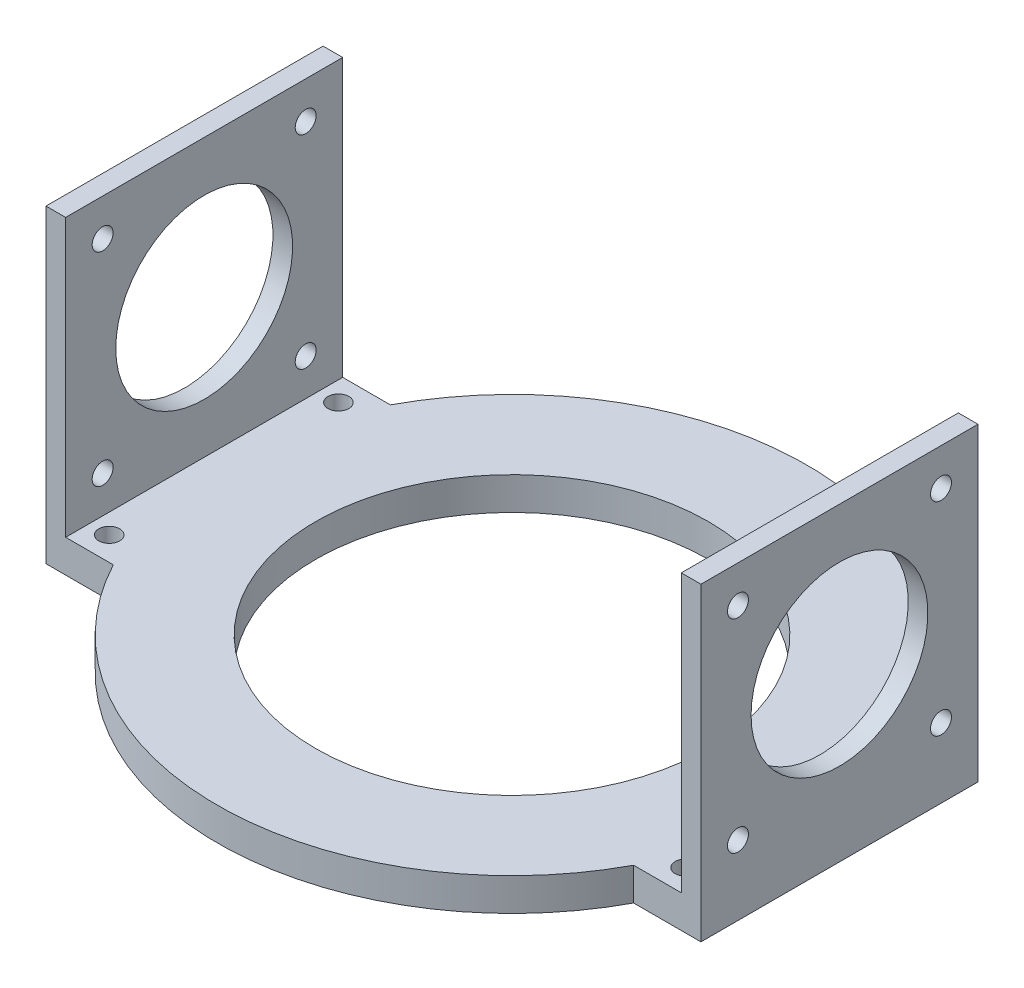
SolidWorks part; units mm, degrees
ref_plane "Front Plane" through (0, 0, 0) normal (0, 0, 1) x (1, 0, 0)
ref_plane "Top Plane" through (0, 0, 0) normal (0, 1, 0) x (1, 0, 0)
ref_plane "Right Plane" through (0, 0, 0) normal (1, 0, 0) x (0, 0, -1)
sketch "Sketch1" plane through (0, 0, 0) normal (0, 1, 0) x (1, 0, 0)
  line L0 (0, 0) -> (-45, 0) construction
  line L1 (0, 0) -> (45, 0) construction
  line L2 (-45, 0) -> (-33, 0) construction
  line L3 (45, 0) -> (33, 0) construction
  line L4 (-16, 21.15) -> (-50, 21.15)
  line L5 (-16, 21.15) -> (-16, -21.15)
  line L6 (-50, 21.15) -> (-50, -21.15)
  line L7 (-16, -21.15) -> (-50, -21.15)
  line L8 (-16, 21.15) -> (-50, -21.15) construction
  line L9 (-50, 21.15) -> (-16, -21.15) construction
  line L10 (16, 21.15) -> (50, 21.15)
  line L11 (16, 21.15) -> (16, -21.15)
  line L12 (50, 21.15) -> (50, -21.15)
  line L13 (16, -21.15) -> (50, -21.15)
  line L14 (16, 21.15) -> (50, -21.15) construction
  line L15 (50, 21.15) -> (16, -21.15) construction
  circle A0 centre (0, 0) radius 45
  circle A1 centre (0, 0) radius 40
  dimension "D1" = 90
  dimension "D8" = 80
  dimension "D2" = 12
  dimension "D3" = 12
  dimension "D4" = 34
  dimension "D5" = 34
  dimension "D6" = 42.3
  dimension "D7" = 42.3
extrude "body" add sketch "Sketch1" along normal blind 5
sketch "Sketch4" plane through (0, 5, 0) normal (0, 1, 0) x (1, 0, 0)
  line L0 (-39.72, -21.15) -> (-50, -21.15) construction
  line L1 (-50, 21.15) -> (-47, 21.15)
  line L2 (-50, 21.15) -> (-50, -21.15)
  line L3 (-50, -21.15) -> (-47, -21.15)
  line L4 (-47, 21.15) -> (-47, -21.15)
  line L5 (39.72, -21.15) -> (50, -21.15) construction
  line L6 (50, 21.15) -> (47, 21.15)
  line L7 (50, 21.15) -> (50, -21.15)
  line L8 (50, -21.15) -> (47, -21.15)
  line L9 (47, 21.15) -> (47, -21.15)
  dimension "D1" = 3
  dimension "D2" = 3
extrude "extrude-wing" add sketch "Sketch4" along normal blind 42.3
sketch "Sketch5" plane through (-50, 0, 0) normal (-1, 0, 0) x (0, 0, 1)
  line L0 (21.15, 47.3) -> (21.15, 0) construction
  line L1 (-21.15, 47.3) -> (21.15, 47.3) construction
  line L2 (-21.15, 47.3) -> (-21.15, 5) construction
  line L3 (-21.15, 5) -> (21.15, 5) construction
  line L4 (21.15, 47.3) -> (21.15, 5) construction
  line L5 (0, 47.3) -> (0, 26.15) construction
  line L7 (-15.5, 41.65) -> (15.5, 41.65) construction
  line L8 (-15.5, 41.65) -> (-15.5, 10.65) construction
  line L9 (-15.5, 10.65) -> (15.5, 10.65) construction
  line L10 (15.5, 41.65) -> (15.5, 10.65) construction
  line L11 (-15.5, 41.65) -> (15.5, 10.65) construction
  line L12 (-15.5, 10.65) -> (15.5, 41.65) construction
  circle A0 centre (-15.5, 41.65) radius 1.6
  circle A1 centre (15.5, 41.65) radius 1.6
  circle A2 centre (15.5, 10.65) radius 1.6
  circle A3 centre (-15.5, 10.65) radius 1.6
  circle A4 centre (0, 26.15) radius 13.5
  dimension "D5" = 3.2
  dimension "D6" = 3.2
  dimension "D7" = 3.2
  dimension "D8" = 3.2
  dimension "D9" = 27
  dimension "D1" = 42.3
  dimension "D2" = 21.15
  dimension "D3" = 31
  dimension "D4" = 31
extrude "cut-motor-holes" cut sketch "Sketch5" against normal through all
sketch "Sketch8" plane through (0, 0, 0) normal (0, -1, 0) x (1, 0, 0)
  circle A0 centre (0, 0) radius 30
  dimension "D1" = 60
extrude "cut-excess-material" cut sketch "Sketch8" against normal up to body separate body
sketch "Sketch9" plane through (0, 5, 0) normal (0, 1, 0) x (1, 0, 0)
  line L0 (-47, 0) -> (47, 0) construction
  line L1 (47, 21.15) -> (47, -21.15) construction
  line L2 (47, 0) -> (44, 0)
  line L4 (-47, 0) -> (-44, 0)
  line L5 (-44, 17.5) -> (-44, -17.5) construction
  line L6 (44, 17.5) -> (44, -17.5) construction
  circle A0 centre (44, -17.5) radius 1.6
  circle A1 centre (44, 17.5) radius 1.6
  circle A2 centre (-44, 17.5) radius 1.6
  circle A3 centre (-44, -17.5) radius 1.6
  point P8 (0, 0)
  point P11 (-44, 0)
  point P13 (44, 0)
  dimension "D5" = 3.2
  dimension "D6" = 3.2
  dimension "D7" = 3.2
  dimension "D8" = 3.2
  dimension "D1" = 3
  dimension "D2" = 3
  dimension "D3" = 35
  dimension "D4" = 35
extrude "cut-deck-holes" cut sketch "Sketch9" against normal up to next contours A0 | A1 | A2 | A3
equation "\"tol\"= .2mm"
